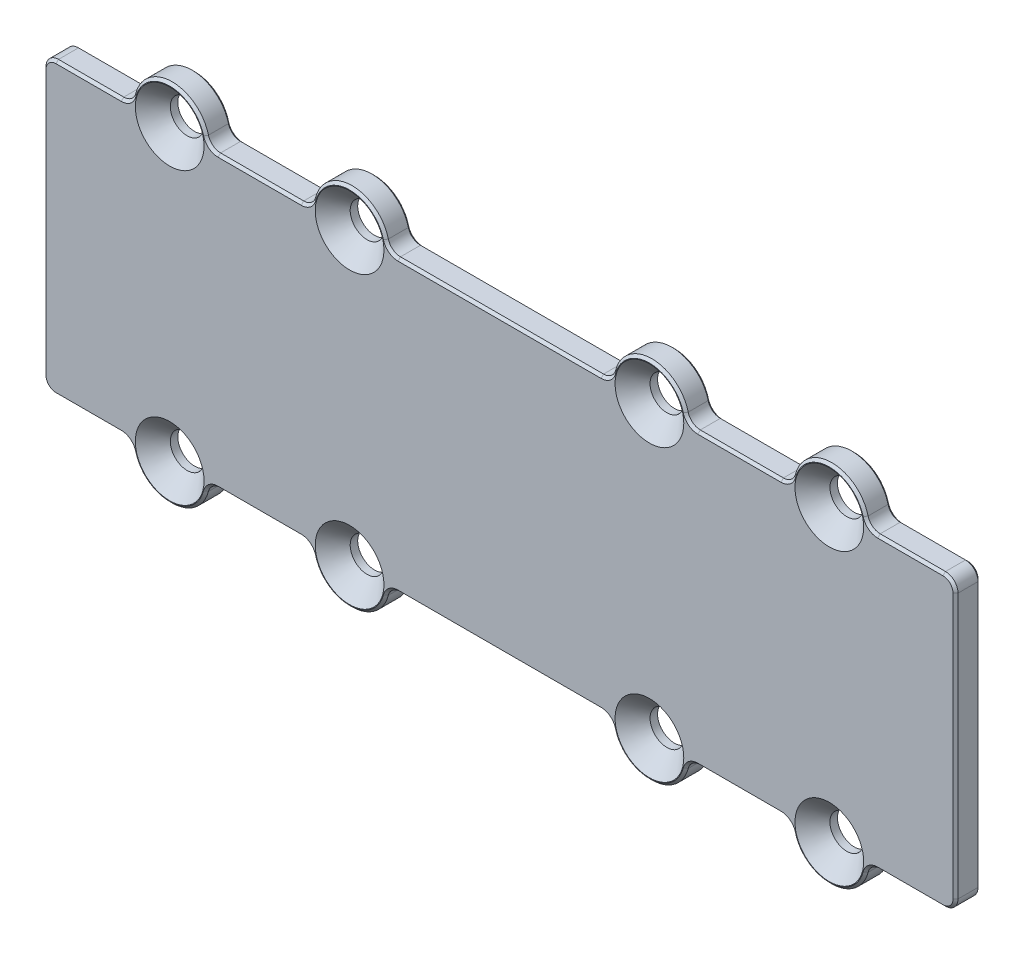
SolidWorks part; units mm, degrees
material "ABS"
ref_plane "前视基准面" through (0, 0, 0) normal (0, 0, 1) x (1, 0, 0)
ref_plane "上视基准面" through (0, 0, 0) normal (0, 1, 0) x (1, 0, 0)
ref_plane "右视基准面" through (0, 0, 0) normal (1, 0, 0) x (0, 0, -1)
other "Configuration Table"
sketch "草图1" plane through (0, 0, 0) normal (0, 0, 1) x (1, 0, 0)
  line L1 (-36.5, 11.6) -> (36.5, 11.6)
  line L2 (-36.5, 11.6) -> (-36.5, -11.6)
  line L3 (-36.5, -11.6) -> (36.5, -11.6)
  line L4 (36.5, 11.6) -> (36.5, -11.6)
  line L5 (0, -11.6) -> (0, 11.6) construction
  line L6 (-36.5, 0) -> (36.5, 0) construction
  line L7 (-12, 11.6) -> (12, 11.6) construction
  line L8 (-12, 11.6) -> (-12, -11.6) construction
  line L9 (-12, -11.6) -> (12, -11.6) construction
  line L10 (12, 11.6) -> (12, -11.6) construction
  line L11 (0, -11.6) -> (0, 11.6) construction
  line L12 (-12, 0) -> (12, 0) construction
  line L13 (-26.4, 11.6) -> (26.4, 11.6)
  line L14 (-26.4, 11.6) -> (-26.4, -11.6) construction
  line L15 (-26.4, -11.6) -> (26.4, -11.6)
  line L16 (26.4, 11.6) -> (26.4, -11.6) construction
  line L17 (0, -11.6) -> (0, 11.6) construction
  line L18 (-26.4, 0) -> (26.4, 0) construction
  circle A0 centre (-26.4, 11.6) radius 3
  circle A1 centre (-12, 11.6) radius 3
  circle A2 centre (12, 11.6) radius 3
  circle A3 centre (26.4, 11.6) radius 3
  circle A4 centre (26.4, -11.6) radius 3
  circle A5 centre (12, -11.6) radius 3
  circle A6 centre (-12, -11.6) radius 3
  circle A7 centre (-26.4, -11.6) radius 3
  point P0 (0, 0)
  point P4 (0, 0)
  point P11 (0, 0)
  dimension "D5" = 6
  dimension "D1" = 73
  dimension "D2" = 23.2
  dimension "D3" = 24
  dimension "D4" = 52.8
extrude "凸台-拉伸1" add sketch "草图1" along normal blind 2 contours L1 A2 | L1 A3 | L15 A4 L3 | L15 A5 | L15 A6 | L3 A7 | A0 | A1
fillet "圆角1" radius 1 20 edges at (9, 11.6, 1) (15, 11.6, 1) (23.4, 11.6, 1) (29.4, 11.6, 1) (36.5, 11.6, 1) (29.4, -11.6, 1) (23.4, -11.6, 1) (15, -11.6, 1) (9, -11.6, 1) (-9, -11.6, 1) (-15, -11.6, 1) (-23.4, -11.6, 1) (-29.4, -11.6, 1) (-36.5, -11.6, 1) (-36.5, 11.6, 1) (-23.4, 11.6, 1) (-29.4, 11.6, 1) (-9, 11.6, 1) (-15, 11.6, 1) (36.5, -11.6, 1)
hole_wizard "M2.5 锥坑平头螺钉的锥形沉头孔1" positions "3D草图1" profile "草图3" countersink size "M2.5" standard "DIN"
sketch3d "3D草图1"
  line L0 (-26.4, 11.6, 2) -> (-26.4, 11.6, 0) construction
  line L1 (-12, 11.6, 2) -> (-12, 11.6, 0) construction
  line L2 (12, 11.6, 2) -> (12, 11.6, 0) construction
  line L3 (26.4, 11.6, 2) -> (26.4, 11.6, 0) construction
  line L4 (26.4, -11.6, 2) -> (26.4, -11.6, 0) construction
  line L5 (12, -11.6, 2) -> (12, -11.6, 0) construction
  line L6 (-12, -11.6, 2) -> (-12, -11.6, 0) construction
  line L7 (-26.4, -11.6, 2) -> (-26.4, -11.6, 0) construction
  point P0 (-26.4, 11.6, 2)
  point P4 (-12, 11.6, 2)
  point P8 (12, 11.6, 2)
  point P12 (26.4, 11.6, 2)
  point P16 (26.4, -11.6, 2)
  point P20 (12, -11.6, 2)
  point P24 (-12, -11.6, 2)
  point P28 (-26.4, -11.6, 2)
sketch "草图3" plane through (-26.4, 11.6, 2) normal (1, 0, 0) x (0, -1, 0)
  line L0 (0, 0) -> (0, 6.35)
  line L1 (0, 6.35) -> (1.35, 5.5388)
  line L2 (1.35, 5.5388) -> (1.35, 1.4)
  line L3 (1.35, 1.4) -> (2.75, 0)
  line L5 (2.75, 0) -> (0, 0)
  line L6 (-1.35, 1.4) -> (-2.75, 0) construction
  line L10 (0, 6.35) -> (-1.35, 5.5388) construction
  line L11 (0, -6.35) -> (0, 107.95) construction
  dimension "孔直径" = 2.7
  dimension "孔深度" = 6.35
  dimension "近端锥形沉头孔直径" = 5.5
  dimension "近端锥形沉头孔角度" = 90
  dimension "导头角度" = 118
sketch "草图4" plane through (0, 0, 2) normal (0, 0, 1) x (1, 0, 0)
  line L0 (-8.127, -11.6) -> (8.127, -11.6) construction
  line L1 (-2.4, 11.6) -> (2.4, 11.6)
  line L2 (-2.4, 11.6) -> (-2.4, -11.6)
  line L3 (-2.4, -11.6) -> (2.4, -11.6)
  line L4 (2.4, 11.6) -> (2.4, -11.6)
  line L5 (0, -11.6) -> (0, 11.6) construction
  line L6 (-2.4, 0) -> (2.4, 0) construction
  point P0 (0, 0)
  dimension "D1" = 4.8
chamfer "倒角1" distance 0.2 angle 45 80 edges at (36.5, 0, 2) (36.2071, 11.3071, 2) (36.2071, -11.3071, 2) (32.8865, 11.6, 2) (32.8865, -11.6, 2) (29.6606, 11.8094, 2) (29.6606, -11.8094, 2) (26.4, 14.6, 2) (26.4, -14.6, 2) (23.1394, 11.8094, 2) (23.1394, -11.8094, 2) (19.2, 11.6, 2) (19.2, -11.6, 2) (15.2606, 11.8094, 2) (15.2606, -11.8094, 2) (12, 14.6, 2) (12, -14.6, 2) (8.7394, 11.8094, 2) (8.7394, -11.8094, 2) (0, 11.6, 2) (0, -11.6, 2) (-8.7394, 11.8094, 2) (-8.7394, -11.8094, 2) (-12, 14.6, 2) (-12, -14.6, 2) (-15.2606, 11.8094, 2) (-15.2606, -11.8094, 2) (-19.2, 11.6, 2) (-19.2, -11.6, 2) (-23.1394, 11.8094, 2) (-23.1394, -11.8094, 2) (-26.4, 14.6, 2) (-26.4, -14.6, 2) (-29.6606, 11.8094, 2) (-29.6606, -11.8094, 2) (-32.8865, 11.6, 2) (-32.8865, -11.6, 2) (-36.2071, 11.3071, 2) (-36.2071, -11.3071, 2) (-36.5, 0, 2) (36.5, 0, 0) (36.2071, 11.3071, 0) (36.2071, -11.3071, 0) (32.8865, 11.6, 0) (32.8865, -11.6, 0) (29.6606, 11.8094, 0) (29.6606, -11.8094, 0) (26.4, 14.6, 0) (26.4, -14.6, 0) (23.1394, 11.8094, 0) (23.1394, -11.8094, 0) (19.2, 11.6, 0) (19.2, -11.6, 0) (15.2606, 11.8094, 0) (15.2606, -11.8094, 0) (12, 14.6, 0) (12, -14.6, 0) (8.7394, 11.8094, 0) (8.7394, -11.8094, 0) (0, 11.6, 0) (0, -11.6, 0) (-8.7394, 11.8094, 0) (-8.7394, -11.8094, 0) (-12, 14.6, 0) (-12, -14.6, 0) (-15.2606, 11.8094, 0) (-15.2606, -11.8094, 0) (-19.2, 11.6, 0) (-19.2, -11.6, 0) (-23.1394, 11.8094, 0) (-23.1394, -11.8094, 0) (-26.4, 14.6, 0) (-26.4, -14.6, 0) (-29.6606, 11.8094, 0) (-29.6606, -11.8094, 0) (-32.8865, 11.6, 0) (-32.8865, -11.6, 0) (-36.2071, 11.3071, 0) (-36.2071, -11.3071, 0) (-36.5, 0, 0)
